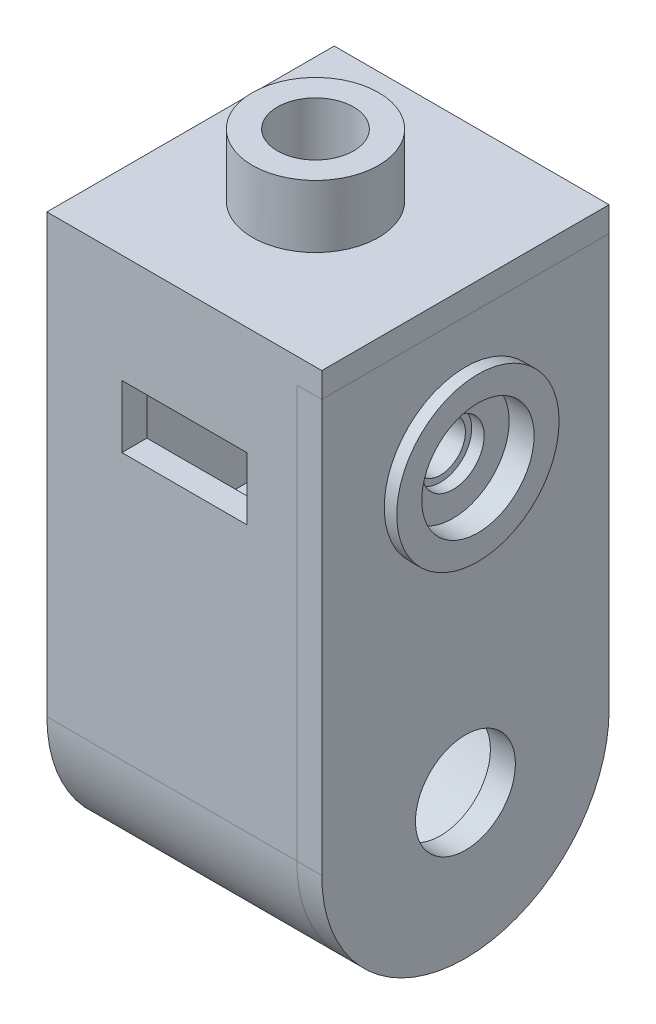
SolidWorks part; units mm, degrees
ref_plane "Front Plane" through (0, 0, 0) normal (0, 0, 1) x (1, 0, 0)
ref_plane "Top Plane" through (0, 0, 0) normal (0, 1, 0) x (1, 0, 0)
ref_plane "Right Plane" through (0, 0, 0) normal (1, 0, 0) x (0, 0, -1)
sketch "Sketch1" plane through (0, 0, 0) normal (0, 1, 0) x (1, 0, 0)
  circle A2 centre (0, 0) radius 3.05
  circle A3 centre (0, 0) radius 5.05
  dimension "D1" = 2
extrude "Boss-Extrude1" add sketch "Sketch1" along normal blind 7
sketch "Sketch2" plane through (0, 0, 0) normal (0, -1, 0) x (1, 0, 0)
  line L0 (-10, 0) -> (10, 0) construction
  line L1 (-10, 11.5) -> (10, 11.5)
  line L2 (-10, -11.5) -> (10, -11.5)
  arc A0 (-10, 11.5) -> (-10, -11.5) centre (-10, 0) ccw
  arc A1 (10, -11.5) -> (10, 11.5) centre (10, 0) ccw
  circle A2 centre (0, 0) radius 3.05
  point P3 (0, 0)
  dimension "D2" = 11.5
  dimension "D1" = 20
extrude "Boss-Extrude2" add sketch "Sketch2" against normal blind 2
sketch "Sketch3" plane through (0, 2, 0) normal (0, 1, 0) x (1, 0, 0)
  line L0 (-10, 0) -> (10, 0) construction
  line L1 (-10, 11.5) -> (10, 11.5)
  line L2 (-10, -11.5) -> (10, -11.5)
  line L3 (-10, 0) -> (10, 0) construction
  line L4 (-10, 9.5) -> (10, 9.5)
  line L5 (-10, -9.5) -> (10, -9.5)
  line L6 (-10, 11.5) -> (-10, 9.5)
  line L7 (10, 11.5) -> (10, 9.5)
  line L8 (-10, -9.5) -> (-10, -11.5)
  line L9 (10, -9.5) -> (10, -11.5)
  point P4 (0, 0)
  point P9 (0, 0)
extrude "Boss-Extrude3" add sketch "Sketch3" against normal blind 35
sketch "Sketch4" plane through (-10, 0, 0) normal (-1, 0, 0) x (0, 0, 1)
  line L0 (-11.5, -33) -> (-9.5, -33)
  line L1 (9.5, -33) -> (11.5, -33)
  arc A0 (-11.5, -33) -> (11.5, -33) centre (0, -33) ccw
  arc A1 (-9.5, -33) -> (9.5, -33) centre (0, -33) ccw
extrude "Boss-Extrude4" add sketch "Sketch4" against normal up to surface (20 mm away) up to face at (10, -16.5, -10.5)
sketch "Sketch5" plane through (0, 0, 9.5) normal (0, 0, -1) x (-1, 0, 0)
  line L0 (10, -24.78) -> (1.9, -24.78)
  line L1 (1.9, -24.78) -> (1.9, -22.78)
  line L4 (10, -33) -> (10, 0) construction
  line L5 (10, -22.78) -> (1.9, -22.78)
  line L6 (10, -24.78) -> (10, -22.78)
  line L8 (-10, -44.5) -> (10, -44.5) construction
  dimension "D1" = 19.72
extrude "Boss-Extrude5" add sketch "Sketch5" along normal up to surface (19 mm away) up to face at (0, -16.5, -9.5)
sketch "Sketch6" plane through (-10, 0, 0) normal (-1, 0, 0) x (0, 0, 1)
  line L0 (2.6933, -24.78) -> (-2.6933, -24.78)
  line L1 (9.5, -24.78) -> (-9.5, -24.78)
  line L2 (9.5, -24.78) -> (9.5, -33)
  line L4 (-9.5, -24.78) -> (-9.5, -33)
  arc A0 (-2.6933, -24.78) -> (2.6933, -24.78) centre (0, -33) ccw
  arc A1 (-9.5, -33) -> (9.5, -33) centre (0, -33) ccw
  line M2 (-9.5, -33) -> (-9.5, -24.78)
  line M3 (-9.5, -24.78) -> (9.5, -24.78)
  line M4 (9.5, -24.78) -> (9.5, -33)
  arc M5 (9.5, -33) -> (-9.5, -33) centre (0, -33) cw
  dimension "D1" = 17.3
extrude "Boss-Extrude6" add sketch "Sketch6" against normal up to surface (8.1 mm away) contours A0 M3 M2 M5 M4 up to face at (-1.9, -23.78, 0)
sketch "Sketch7" plane through (-10, 0, 0) normal (-1, 0, 0) x (0, 0, 1)
  line L1 (-11.5, 2) -> (11.5, 2)
  line L2 (-11.5, 2) -> (-11.5, -33)
  line L4 (11.5, 2) -> (11.5, -33)
  arc A0 (-11.5, -33) -> (11.5, -33) centre (0, -33) ccw
extrude "Boss-Extrude7" add sketch "Sketch7" against normal blind 2
sketch "Sketch8" plane through (-10, 0, 0) normal (-1, 0, 0) x (0, 0, 1)
  circle A0 centre (0, -33) radius 3.9
  dimension "D1" = 7.8
extrude "Boss-Extrude8" add sketch "Sketch8" along normal blind 7
sketch "Sketch9" plane through (-8, 0, 0) normal (1, 0, 0) x (0, 0, -1)
  line L0 (-11.5, 0) -> (11.5, 0) construction
  circle A0 centre (0, -10) radius 4
  dimension "D1" = 8
  dimension "D2" = 10
extrude "Boss-Extrude9" add sketch "Sketch9" along normal up to surface (18 mm away) up to face at (10, -19.125, 0)
sketch "Sketch10" plane through (10, 0, 0) normal (1, 0, 0) x (0, 0, -1)
  circle A0 centre (0, -10) radius 2
  dimension "D1" = 4
extrude "Cut-Extrude1" cut sketch "Sketch10" against normal blind 6 draft 2
sketch "Sketch11" plane through (10, 0, 0) normal (1, 0, 0) x (0, 0, -1)
  line L1 (-11.5, 0) -> (11.5, 0)
  line L2 (-11.5, 0) -> (-11.5, -33)
  line L4 (11.5, 0) -> (11.5, -33)
  arc A0 (-11.5, -33) -> (11.5, -33) centre (0, -33) ccw
extrude "Boss-Extrude10" add sketch "Sketch11" along normal blind 2 separate body
sketch "Sketch12" plane through (0, 0, 0) normal (0, -1, 0) x (1, 0, 0)
  line L0 (-10, 11.5) -> (-10, -11.5)
  line L1 (12, 11.3248) -> (12, -11.3248)
  line L2 (-2.9154, -16.6695) -> (-2.7931, -16.6695)
  arc A0 (-10, 11.5) -> (-10, -11.5) centre (-10, 0) ccw
  arc A1 (12, -11.3248) -> (12, 11.3248) centre (10, 0) ccw
extrude "Cut-Extrude2" cut sketch "Sketch12" against normal blind 2 contours L1 A1
sketch "Sketch13" plane through (0, 2, 0) normal (0, 1, 0) x (1, 0, 0)
  line L1 (-10, 11.5) -> (12, 11.5)
  line L2 (-10, 11.5) -> (-10, -11.5)
  line L3 (-10, -11.5) -> (12, -11.5)
  line L4 (12, 11.5) -> (12, -11.5)
  circle A0 centre (0, 0) radius 5.05
extrude "Boss-Extrude11" add sketch "Sketch13" against normal blind 2
sketch "Sketch14" plane through (12, 0, 0) normal (1, 0, 0) x (0, 0, -1)
  circle A0 centre (0, -10) radius 2.5
  dimension "D1" = 5
extrude "Cut-Extrude3" cut sketch "Sketch14" against normal blind 2
sketch "Sketch15" plane through (12, 0, 0) normal (1, 0, 0) x (0, 0, -1)
  circle A0 centre (0, -10) radius 4.5
  circle A1 centre (0, -10) radius 2.5
  dimension "D1" = 5
  dimension "D2" = 2
extrude "Cut-Extrude4" cut sketch "Sketch15" against normal blind 1
sketch "Sketch16" plane through (12, 0, 0) normal (1, 0, 0) x (0, 0, -1)
  circle A0 centre (0, -10) radius 4.5
  circle A1 centre (0, -10) radius 6.5
  dimension "D1" = 9
  dimension "D2" = 2
extrude "Boss-Extrude12" add sketch "Sketch16" along normal blind 1
sketch "Sketch18" plane through (12, 0, 0) normal (1, 0, 0) x (0, 0, -1)
  circle A0 centre (0, -33) radius 4
  dimension "D1" = 8
extrude "Cut-Extrude6" cut sketch "Sketch18" against normal blind 2
sketch "Sketch19" plane through (0, 0, -11.5) normal (0, 0, -1) x (-1, 0, 0)
  line L0 (-10, -14) -> (8, -14) construction
  line L2 (-6, -6.6841) -> (4, -6.6841)
  line L3 (-6, -6.6841) -> (-6, -11.6841)
  line L4 (-6, -11.6841) -> (4, -11.6841)
  line L5 (4, -6.6841) -> (4, -11.6841)
  point P8 (-1, -14)
  point P9 (-1, -11.6841)
  dimension "D1" = 5
  dimension "D2" = 10
extrude "Cut-Extrude7" cut sketch "Sketch19" against normal blind 2
sketch "Sketch20" plane through (0, 0, 11.5) normal (0, 0, 1) x (1, 0, 0)
  line L1 (6, -11.6841) -> (-4, -11.6841)
  line L2 (6, -11.6841) -> (6, -6.6841)
  line L3 (6, -6.6841) -> (-4, -6.6841)
  line L4 (-4, -11.6841) -> (-4, -6.6841)
extrude "Cut-Extrude8" cut sketch "Sketch20" against normal blind 2
sketch "Sketch21" plane through (10, 0, 0) normal (1, 0, 0) x (0, 0, -1)
  line L1 (-11.5, 0) -> (11.5, 0)
  line L2 (-11.5, 0) -> (-11.5, -33)
  line L4 (11.5, 0) -> (11.5, -33)
  arc A0 (-11.5, -33) -> (11.5, -33) centre (0, -33) ccw
  circle A1 centre (0, -10) radius 2
  dimension "D1" = 4
extrude "Boss-Extrude13" add sketch "Sketch21" along normal blind 2 separate body
delete or keep bodies "Body-Delete/Keep 1" type delete bodies bodies 121
